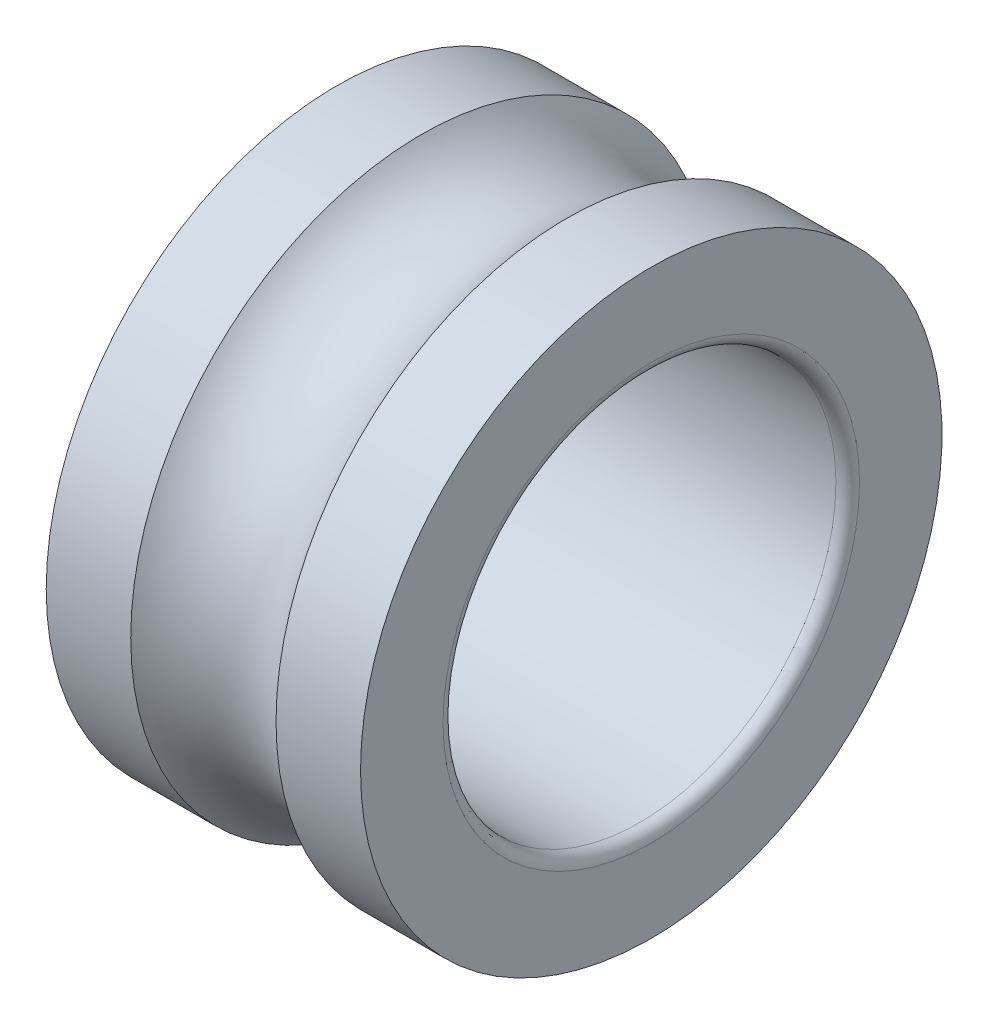
SolidWorks part; units mm, degrees
ref_plane "Front Plane" through (0, 0, 0) normal (0, 0, 1) x (1, 0, 0)
ref_plane "Top Plane" through (0, 0, 0) normal (0, 1, 0) x (1, 0, 0)
ref_plane "Right Plane" through (0, 0, 0) normal (1, 0, 0) x (0, 0, -1)
ref_plane "Plane1" through (0, 0, 0) normal (0, 0, 1) x (1, 0, 0)
sketch "Sketch1" plane through (0, 0, 0) normal (0, 0, 1) x (1, 0, 0)
  line L0 (0.3, 5) -> (7.7, 5)
  line L1 (8, 5.3) -> (8, 7.4)
  line L2 (8, 7.4) -> (5.8491, 7.4)
  line L3 (2.1509, 7.4) -> (0, 7.4)
  line L4 (0, 7.4) -> (0, 5.3)
  line L5 (50, 0) -> (-50, 0) construction
  arc A0 (0, 5.3) -> (0.3, 5) centre (0.3, 5.3) ccw
  arc A1 (7.7, 5) -> (8, 5.3) centre (7.7, 5.3) ccw
  arc A2 (5.8491, 7.4) -> (2.1509, 7.4) centre (4, 8.9) cw
revolve "Revolve1" add sketch "Sketch1" angle 360 about L5
